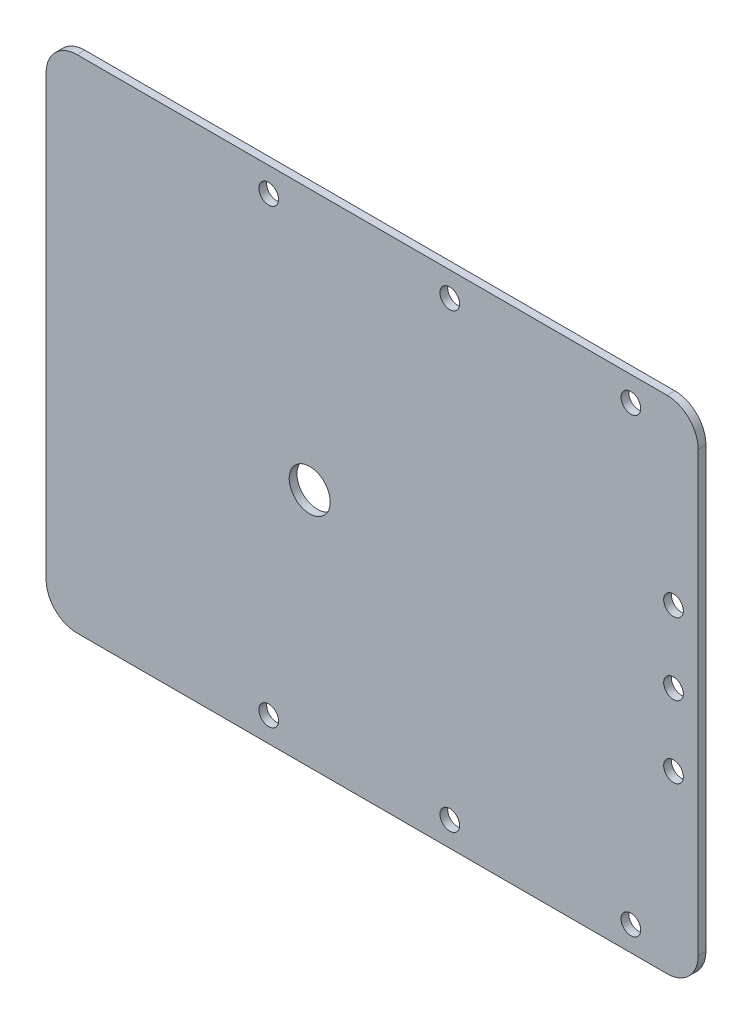
SolidWorks part; units mm, degrees
material "CNC Madness CF"
ref_plane "Front Plane" through (0, 0, 0) normal (0, 0, 1) x (1, 0, 0)
ref_plane "Top Plane" through (0, 0, 0) normal (0, 1, 0) x (1, 0, 0)
ref_plane "Right Plane" through (0, 0, 0) normal (1, 0, 0) x (0, 0, -1)
sketch "Sketch1" plane through (0, 0, 0) normal (0, 0, 1) x (1, 0, 0)
  line L1 (64.275, 9.525) -> (64.275, -87.3)
  line L2 (-61.75, 9.525) -> (64.275, 9.525) construction
  line L3 (-61.75, 9.525) -> (64.275, 9.525)
  line L4 (-61.75, -87.3) -> (64.275, -87.3) construction
  line L5 (-61.75, -87.3) -> (64.275, -87.3)
  line L6 (-61.75, 9.525) -> (-61.75, -87.3)
extrude "Boss-Extrude1" add sketch "Sketch1" along normal blind 1.5
ref_plane "Midplane" through (0, -38.8875, 0) normal (0, 1, 0) x (1, 0, 0)
sketch "Sketch2" plane through (0, 0, 1.5) normal (0, 0, 1) x (1, 0, 0)
  circle A0 centre (51.275, 4.7625) radius 1.4732 construction
  circle A1 centre (51.275, 4.7625) radius 1.4732 construction
  point P4 (51.275, 4.7625)
hole_wizard "#6 Clearance Hole1" positions "Sketch3" profile "Sketch5" hole size "#6" standard "ANSI Inch" end condition through all
sketch "Sketch3" plane through (0, 0, 1.5) normal (0, 0, 1) x (1, 0, 0)
  point P0 (51.275, 4.7625)
sketch "Sketch5" plane through (51.275, 4.7625, 1.5) normal (1, 0, 0) x (0, -1, 0)
  line L0 (0, 0) -> (0, 1.5)
  line L1 (0, 1.5) -> (1.8986, 1.5)
  line L2 (1.8986, 1.5) -> (1.8986, 0)
  line L5 (1.8986, 0) -> (0, 0)
  line L11 (0, -6.35) -> (0, 107.95) construction
  dimension "Thru Hole Dia." = 3.7973
  dimension "Thru Hole Depth" = 1.5
pattern_linear "Sidepanel Pattern" count 3 spacing 35 along (-1, 0, 0) of "#6 Clearance Hole1"
mirror "Mirror1" about plane through (0, -38.8875, 0) normal (0, 1, 0) of "Sidepanel Pattern", "#6 Clearance Hole1"
sketch "Sketch6" plane through (0, 0, 1.5) normal (0, 0, 1) x (1, 0, 0)
  circle A0 centre (59.5125, -25) radius 1.4732 construction
  circle A1 centre (59.5125, -25) radius 1.4732 construction
  point P4 (59.5125, -25)
hole_wizard "#6 Clearance Hole2" positions "Sketch7" profile "Sketch8" hole size "#6" standard "ANSI Inch" end condition through all
sketch "Sketch7" plane through (0, 0, 1.5) normal (0, 0, 1) x (1, 0, 0)
  point P0 (59.5125, -25)
sketch "Sketch8" plane through (59.5125, -25, 1.5) normal (1, 0, 0) x (0, -1, 0)
  line L0 (0, 0) -> (0, 1.5)
  line L1 (0, 1.5) -> (1.8986, 1.5)
  line L2 (1.8986, 1.5) -> (1.8986, 0)
  line L5 (1.8986, 0) -> (0, 0)
  line L11 (0, -6.35) -> (0, 107.95) construction
  dimension "Thru Hole Dia." = 3.7973
  dimension "Thru Hole Depth" = 1.5
pattern_linear "LPattern2" count 3 spacing 13.8875 along (0, -1, 0) of "#6 Clearance Hole2"
fillet "Fillet1" radius 6 4 edges at (-61.75, 9.525, 0.75) (64.275, -87.3, 0.75) (-61.75, -87.3, 0.75) (64.275, 9.525, 0.75)
sketch "Sketch9" plane through (0, 0, 1.5) normal (0, 0, 1) x (1, 0, 0)
  circle A0 centre (-10.8009, -40.8875) radius 3.9624 construction
  circle A1 centre (-10.8009, -40.8875) radius 3.9624
extrude "Cut-Extrude1" cut sketch "Sketch9" against normal through all
equation "\"D3@LPattern2\"=\"D3@Sketch4@P-0003-W - FRONT PANEL-1.Part\"/2"
equation "\"D3@Sidepanel Pattern\"=\"top_sidepanel_hole_spacing@A-0000-N - ROOT LOCUS.Assembly\""
